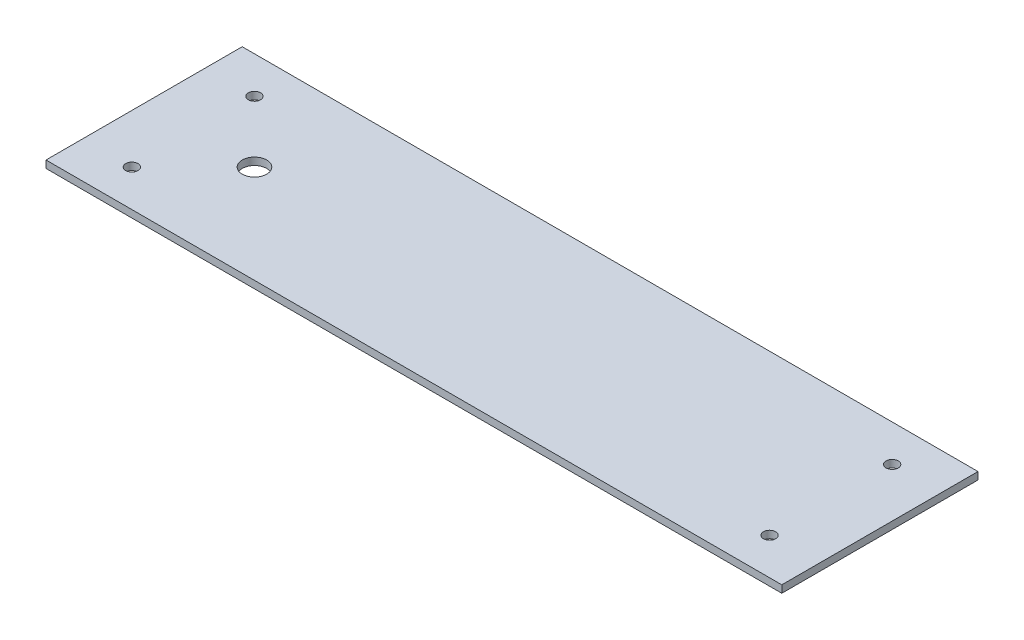
SolidWorks part; units mm, degrees
material "1060 Alloy"
ref_plane "Front Plane" through (0, 0, 0) normal (0, 0, 1) x (1, 0, 0)
ref_plane "Top Plane" through (0, 0, 0) normal (0, 1, 0) x (1, 0, 0)
ref_plane "Right Plane" through (0, 0, 0) normal (1, 0, 0) x (0, 0, -1)
sketch "Sketch1" plane through (0, 0, 0) normal (0, 1, 0) x (1, 0, 0)
  line L1 (-150.2794, 39.6878) -> (149.7206, 39.6878)
  line L2 (-150.2794, 39.6878) -> (-150.2794, -40.3122)
  line L3 (-150.2794, -40.3122) -> (149.7206, -40.3122)
  line L4 (149.7206, 39.6878) -> (149.7206, -40.3122)
  circle A0 centre (-130.2794, 24.6878) radius 2.5
  circle A1 centre (-130.2794, -25.3122) radius 2.5
  circle A2 centre (129.7206, 24.6878) radius 2.5
  circle A3 centre (129.7206, -25.3122) radius 2.5
  circle A4 centre (-105.2794, -0.3122) radius 5
  dimension "D3" = 15
  dimension "D1" = 80
  dimension "D2" = 300
  dimension "D4" = 15
  dimension "D5" = 15
  dimension "D6" = 15
  dimension "D7" = 20
  dimension "D8" = 20
  dimension "D9" = 20
  dimension "D10" = 20
  dimension "D11" = 45
  dimension "D12" = 40
extrude "Boss-Extrude1" add sketch "Sketch1" along normal blind 3
